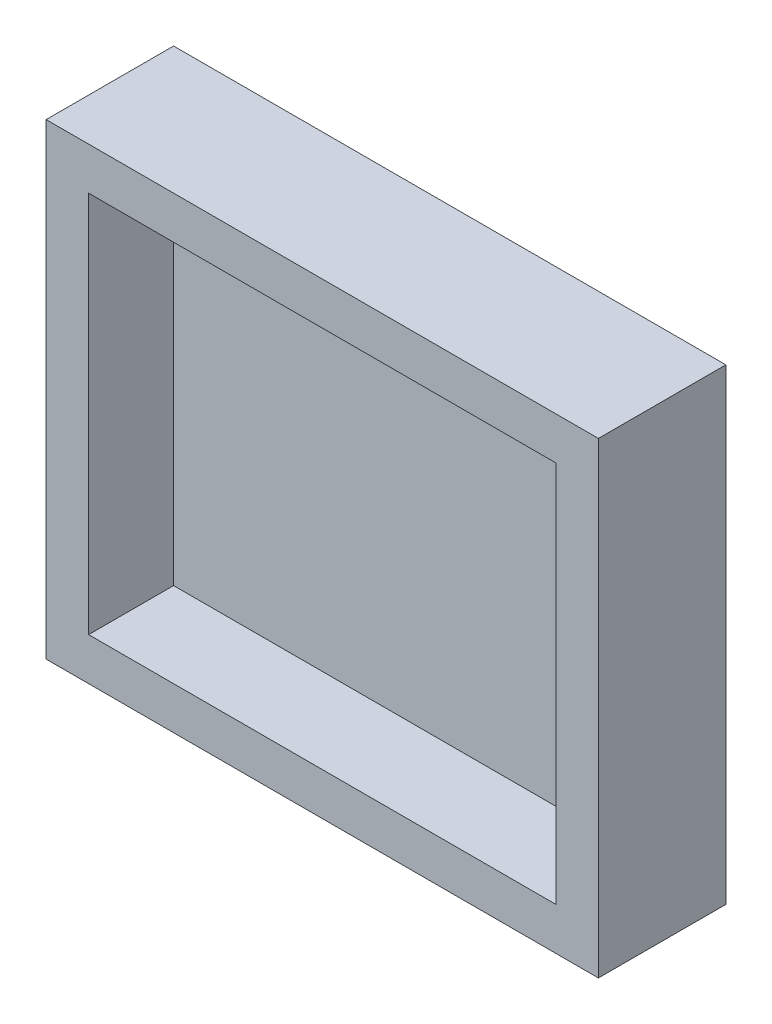
SolidWorks part; units mm, degrees
ref_plane "Plan de face" through (0, 0, 0) normal (0, 0, 1) x (1, 0, 0)
ref_plane "Plan de dessus" through (0, 0, 0) normal (0, 1, 0) x (1, 0, 0)
ref_plane "Plan de droite" through (0, 0, 0) normal (1, 0, 0) x (0, 0, -1)
sketch "Esquisse1" plane through (0, 0, 0) normal (0, 0, 1) x (1, 0, 0)
  line L1 (-32.5, -27.5) -> (32.5, -27.5)
  line L2 (-32.5, -27.5) -> (-32.5, 27.5)
  line L3 (-32.5, 27.5) -> (32.5, 27.5)
  line L4 (32.5, -27.5) -> (32.5, 27.5)
  line L5 (-32.5, -27.5) -> (32.5, 27.5) construction
  line L6 (-32.5, 27.5) -> (32.5, -27.5) construction
  point P0 (0, 0)
  dimension "D1" = 65
  dimension "D2" = 55
extrude "Boss.-Extru.1" add sketch "Esquisse1" along normal blind 15 contours L2 L3 L4 L1
sketch "Esquisse2" plane through (0, 0, 15) normal (0, 0, 1) x (1, 0, 0)
  line L0 (-32.5, -27.5) -> (-32.5, 27.5) construction
  line L1 (-27.5, -22.5) -> (27.5, -22.5)
  line L2 (-27.5, -22.5) -> (-27.5, 22.5)
  line L3 (-27.5, 22.5) -> (27.5, 22.5)
  line L4 (27.5, -22.5) -> (27.5, 22.5)
  line L5 (-27.5, -22.5) -> (27.5, 22.5) construction
  line L6 (-27.5, 22.5) -> (27.5, -22.5) construction
  line L7 (-32.5, 27.5) -> (32.5, 27.5) construction
  point P0 (0, 0)
  dimension "D1" = 5
  dimension "D2" = 5
extrude "Enlèv. mat.-Extru.1" cut sketch "Esquisse2" against normal blind 10
